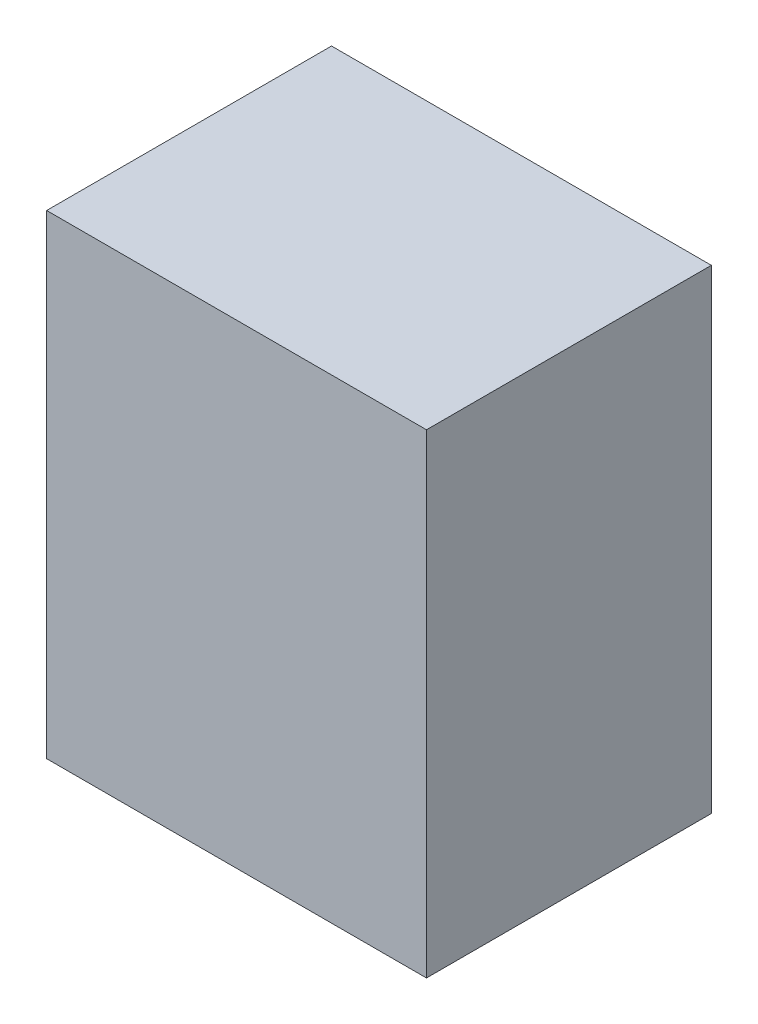
SolidWorks part; units mm, degrees
ref_plane "Front Plane" through (0, 0, 0) normal (0, 0, 1) x (1, 0, 0)
ref_plane "Top Plane" through (0, 0, 0) normal (0, 1, 0) x (1, 0, 0)
ref_plane "Right Plane" through (0, 0, 0) normal (1, 0, 0) x (0, 0, -1)
sketch "Sketch1" plane through (0, 0, 0) normal (0, 0, 1) x (1, 0, 0)
  line L1 (0, 0) -> (8, 0)
  line L2 (0, 0) -> (0, 10)
  line L3 (0, 10) -> (8, 10)
  line L4 (8, 0) -> (8, 10)
  dimension "D1" = 8
  dimension "D2" = 10
extrude "Profile" add sketch "Sketch1" along normal blind 6
equation "\"Profile_Depth\"= 6mm"
equation "\"D1@Profile\" = \"Profile_Depth\""
equation "\"Profile_Sketch_1\"= 8mm"
equation "\"D1@Sketch1\" = \"Profile_Sketch_1\""
equation "\"Profile_Sketch_2\"= 10mm"
equation "\"D2@Sketch1\" = \"Profile_Sketch_2\""
equation "\"EnvelopeWidth\"= 8mm"
equation "\"EnvelopeHeight\"= 10mm"
